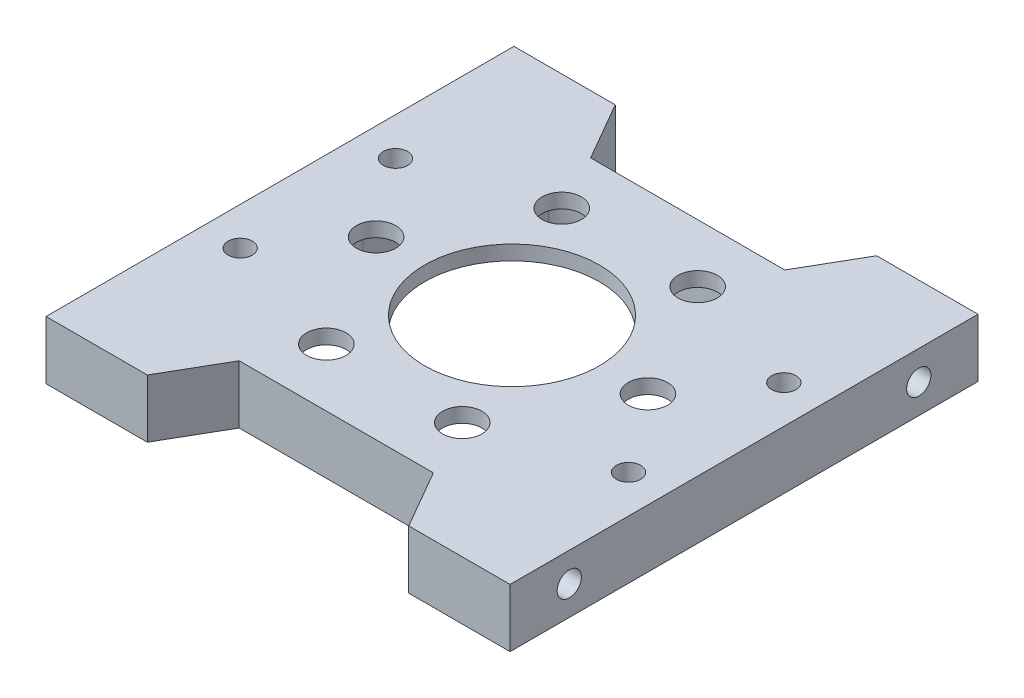
SolidWorks part; units mm, degrees
ref_plane "前视基准面" through (0, 0, 0) normal (0, 0, 1) x (1, 0, 0)
ref_plane "上视基准面" through (0, 0, 0) normal (0, 1, 0) x (1, 0, 0)
ref_plane "右视基准面" through (0, 0, 0) normal (1, 0, 0) x (0, 0, -1)
sketch "草图1" plane through (0, 0, 0) normal (0, 1, 0) x (1, 0, 0)
  line L0 (0, 0) -> (0, 51.3018) construction
  line L1 (0, 0) -> (42.9054, 0) construction
  line L2 (-16, 20.2553) -> (-16, -13.0812) construction
  circle A0 centre (0, 0) radius 14 construction
  circle A1 centre (14, 0) radius 2.025
  circle A2 centre (7, -12.1244) radius 2.025
  circle A3 centre (-7, -12.1244) radius 2.025
  circle A4 centre (-14, 0) radius 2.025
  circle A5 centre (-7, 12.1244) radius 2.025
  circle A6 centre (7, 12.1244) radius 2.025
  circle A7 centre (0, 0) radius 35
  circle A8 centre (0, 0) radius 9
  circle A9 centre (-20, 8) radius 1.25
  circle A10 centre (-20, -8) radius 1.25
  circle A11 centre (20, -8) radius 1.25
  circle A12 centre (20, 8) radius 1.25
  point P17 (0, 0)
  dimension "D1" = 28
  dimension "D2" = 4.05
  dimension "D4" = 70
  dimension "D5" = 18
  dimension "D6" = 2.5
  dimension "D7" = 16
  dimension "D8" = 4
  dimension "D9" = 40
  dimension "D3" = 6
extrude "凸台-拉伸1" add sketch "草图1" along normal mid plane 6
sketch "草图2" plane through (0, 3, 0) normal (0, 1, 0) x (1, 0, 0)
  line L0 (0, 0) -> (0, 35) construction
  line L1 (-23.9, 25.5693) -> (-23.9, -25.5693)
  line L2 (23.9, 25.5693) -> (23.9, -25.5693)
  line L3 (-23.9, 24.1) -> (-25.3809, 24.1)
  line L4 (23.9, 24.1) -> (25.3809, 24.1)
  line L5 (0, 0) -> (44.5829, 0) construction
  line L6 (-23.9, -24.1) -> (-25.3809, -24.1)
  line L7 (23.9, -24.1) -> (25.3809, -24.1)
  line L8 (-23.9, 24.1) -> (23.9, 24.1)
  line L9 (-23.9, -24.1) -> (23.9, -24.1)
  circle A0 centre (-20, 8) radius 1.25 construction
  circle A1 centre (0, 0) radius 35
  circle A2 centre (0, 0) radius 35
  circle A3 centre (-20, 8) radius 1.25 construction
  circle M13 centre (0, 0) radius 35
  dimension "D2" = 3.9
  dimension "D3" = 48.2
  dimension "D1" = 0
extrude "切除-拉伸1" cut sketch "草图2" against normal up to next contours L1 M13 | L2 M13 | L1 L8 L2 M13 | L3 L1 M13 | L2 L4 M13 | L1 L6 M13 | L9 L1 L2 M13 | L7 L2 M13
sketch "草图3" plane through (-23.9, 0, 0) normal (-1, 0, 0) x (0, 0, 1)
  line L0 (0, 0) -> (0, 13.1859) construction
  circle A0 centre (18, 0) radius 1.25
  circle A1 centre (-18, 0) radius 1.25
  dimension "D1" = 2.5
  dimension "D2" = 36
extrude "切除-拉伸2" cut sketch "草图3" against normal blind 8
sketch "草图5" plane through (0, -3, 0) normal (0, -1, 0) x (1, 0, 0)
  line L0 (-7, 15.8744) -> (7, 15.8744)
  line L1 (10.2476, 13.9994) -> (17.2476, 1.875)
  line L2 (17.2476, -1.875) -> (10.2476, -13.9994)
  line L3 (7, -15.8744) -> (-7, -15.8744)
  line L4 (-10.2476, -13.9994) -> (-17.2476, -1.875)
  line L5 (-17.2476, 1.875) -> (-10.2476, 13.9994)
  circle A0 centre (-7, 12.1244) radius 3.75
  circle A2 centre (7, 12.1244) radius 3.75
  circle A3 centre (14, 0) radius 3.75
  circle A4 centre (7, -12.1244) radius 3.75
  circle A5 centre (-7, -12.1244) radius 3.75
  circle A6 centre (-14, 0) radius 3.75
  point P16 (0, 0)
  point P28 (0, 0)
  circle M1 centre (14, 0) radius 2.025
  circle M2 centre (0, 0) radius 9
  circle M3 centre (7, 12.1244) radius 2.025
  circle M4 centre (-7, 12.1244) radius 2.025
  circle M5 centre (-14, 0) radius 2.025
  circle M6 centre (-7, -12.1244) radius 2.025
  circle M7 centre (7, -12.1244) radius 2.025
  dimension "D1" = 7.5
  dimension "D3" = 6
  dimension "D2" = 6
extrude "切除-拉伸4" cut sketch "草图5" against normal blind 4.5 contours A6 L4 A5 L3 A4 L2 A3 L1 A2 L0 A0 L5 M2 | A6 M5 | A0 M4 | A2 M3 | A3 M1 | A4 M7 | A5 M6
mirror "镜向1" about plane through (0, 0, 0) normal (1, 0, 0) of "切除-拉伸2"
sketch "草图7" plane through (0, -3, 0) normal (0, -1, 0) x (1, 0, 0)
  line L0 (-50, 0) -> (50, 0) construction
  line L1 (0, -50) -> (0, 50) construction
  line L2 (-13.4641, 24.1) -> (-10, 18.1)
  line L3 (23.9, 24.1) -> (-23.9, 24.1) construction
  line L4 (13.4641, 24.1) -> (10, 18.1)
  line L5 (-13.4641, 24.1) -> (13.4641, 24.1)
  line L6 (10, 18.1) -> (-10, 18.1)
  line L7 (10, -18.1) -> (-10, -18.1)
  line L8 (-13.4641, -24.1) -> (13.4641, -24.1)
  line L9 (13.4641, -24.1) -> (10, -18.1)
  line L10 (-13.4641, -24.1) -> (-10, -18.1)
  dimension "D1" = 60
  dimension "D2" = 6
  dimension "D3" = 20
extrude "切除-拉伸6" cut sketch "草图7" against normal through all
